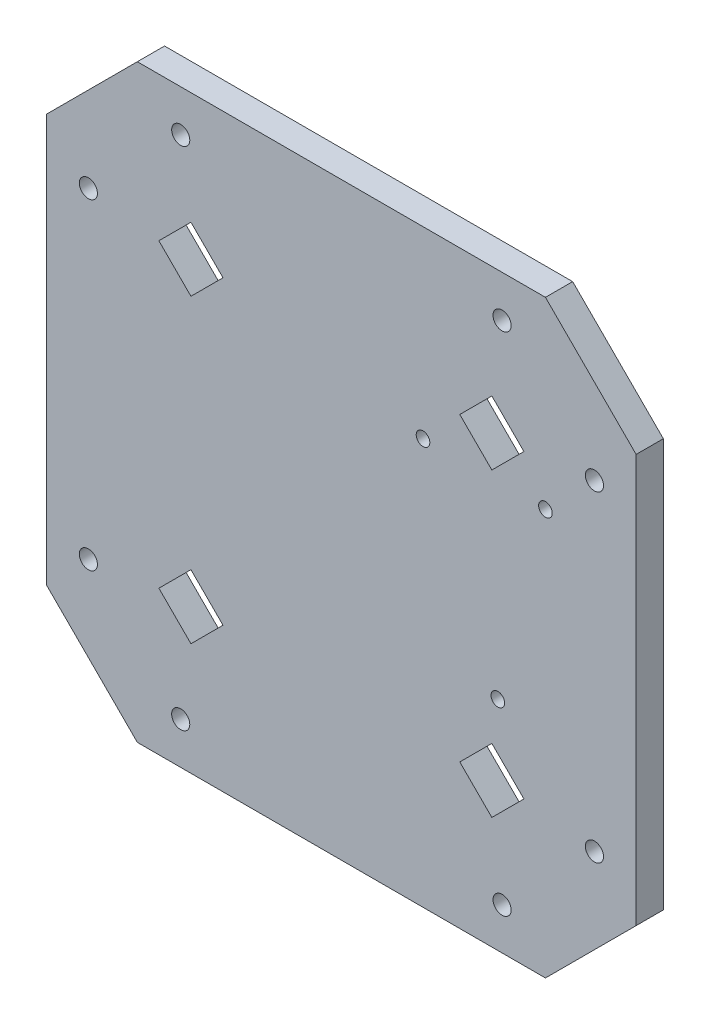
SolidWorks part; units mm, degrees
ref_plane "前基準面" through (0, 0, 0) normal (0, 0, 1) x (1, 0, 0)
ref_plane "上基準面" through (0, 0, 0) normal (0, 1, 0) x (1, 0, 0)
ref_plane "右基準面" through (0, 0, 0) normal (1, 0, 0) x (0, 0, -1)
sketch "草圖1" plane through (0, 0, 0) normal (0, 0, 1) x (1, 0, 0)
  line L2 (0, 0) -> (0, 130)
  line L4 (-130, 0) -> (-130, 130)
  line L5 (-130, 130) -> (0, 130)
  line L37 (-130, 0) -> (0, 0)
  dimension "D2" = 130
  dimension "D3" = 130
extrude "填料-伸長1" add sketch "草圖1" along normal blind 6
ref_plane "平面1" through (0, 0, -35.9) normal (0, 0, 1) x (1, 0, 0)
sketch "草圖10" plane through (0, 0, 6) normal (0, 0, 1) x (1, 0, 0)
  line L0 (0, 0) -> (0, 130) construction
  line L1 (-38.8909, 98.1802) -> (-31.8198, 105.2513)
  line L2 (-38.8909, 98.1802) -> (-31.8198, 91.1091)
  line L3 (-31.8198, 91.1091) -> (-24.7487, 98.1802)
  line L4 (-31.8198, 105.2513) -> (-24.7487, 98.1802)
  line L6 (-28.2843, 101.7157) -> (0, 130) construction
  line L8 (-65, 130) -> (-65, 0) construction
  line L9 (0, 130) -> (-130, 130) construction
  line L10 (-130, 0) -> (0, 0) construction
  line L11 (-101.7157, 101.7157) -> (-130, 130) construction
  line L12 (-130, 130) -> (-130, 0) construction
  line L13 (-130, 65) -> (0, 65) construction
  line L14 (-98.1802, 105.2513) -> (-105.2513, 98.1802)
  line L15 (-98.1802, 91.1091) -> (-105.2513, 98.1802)
  line L16 (-91.1091, 98.1802) -> (-98.1802, 91.1091)
  line L17 (-91.1091, 98.1802) -> (-98.1802, 105.2513)
  line L18 (-101.7157, 28.2843) -> (-130, 0) construction
  line L19 (-28.2843, 28.2843) -> (0, 0) construction
  line L20 (-91.1091, 31.8198) -> (-98.1802, 24.7487)
  line L21 (-91.1091, 31.8198) -> (-98.1802, 38.8909)
  line L22 (-98.1802, 38.8909) -> (-105.2513, 31.8198)
  line L23 (-98.1802, 24.7487) -> (-105.2513, 31.8198)
  line L24 (-31.8198, 24.7487) -> (-24.7487, 31.8198)
  line L25 (-31.8198, 38.8909) -> (-24.7487, 31.8198)
  line L26 (-38.8909, 31.8198) -> (-31.8198, 38.8909)
  line L27 (-38.8909, 31.8198) -> (-31.8198, 24.7487)
  dimension "D4" = 135
  dimension "D6" = 45
  dimension "D2" = 10
  dimension "D3" = 10
  dimension "D5" = 40
  dimension "D1" = 10
extrude "除料-伸長1" cut sketch "草圖10" against normal up to surface (6 mm away) up to face at (-65, 65, 0)
sketch "草圖11" plane through (0, 0, 6) normal (0, 0, 1) x (1, 0, 0)
  line L0 (-29.5647, 120.8) -> (-29.5647, 130) construction
  line L1 (0, 130) -> (-130, 130) construction
  line L2 (-65, 130) -> (-65, 0) construction
  line L3 (-130, 0) -> (0, 0) construction
  line L4 (-65, 0) -> (-130, 65) construction
  line L5 (-9.1804, 98.4354) -> (-9.2, 100.4353) construction
  line L6 (-9.2, 100.4353) -> (0, 100.4353) construction
  line L7 (0, 0) -> (0, 130) construction
  line L8 (-130, 130) -> (-130, 0) construction
  line L9 (-130, 65) -> (0, 65) construction
  line L10 (-120.8, 100.4353) -> (-130, 100.4353) construction
  line L11 (-120.8196, 98.4354) -> (-120.8, 100.4353) construction
  line L12 (-100.4353, 120.8) -> (-100.4353, 130) construction
  line L13 (-100.4353, 9.2) -> (-100.4353, 0) construction
  line L14 (-120.8196, 31.5646) -> (-120.8, 29.5647) construction
  line L15 (-120.8, 29.5647) -> (-130, 29.5647) construction
  line L16 (-9.2, 29.5647) -> (0, 29.5647) construction
  line L17 (-9.1804, 31.5646) -> (-9.2, 29.5647) construction
  line L18 (-29.5647, 9.2) -> (-29.5647, 0) construction
  circle A0 centre (-9.2, 100.4353) radius 2
  circle A1 centre (-29.5647, 120.8) radius 2
  circle A2 centre (-100.4353, 120.8) radius 2
  circle A3 centre (-120.8, 100.4353) radius 2
  circle A4 centre (-120.8, 29.5647) radius 2
  circle A5 centre (-100.4353, 9.2) radius 2
  circle A6 centre (-29.5647, 9.2) radius 2
  circle A7 centre (-9.2, 29.5647) radius 2
  dimension "D1" = 9.2
  dimension "D4" = 28.8
  dimension "D6" = 4
  dimension "D8" = 4
extrude "除料-伸長2" cut sketch "草圖11" against normal up to next
chamfer "導角1" distance 20 angle 45 4 edges at (0, 130, 3) (0, 0, 3) (-130, 0, 3) (-130, 130, 3)
sketch "草圖12" plane through (0, 0, 6) normal (0, 0, 1) x (1, 0, 0)
  line L0 (-47, 89.5) -> (-47, 40.5) construction
  line L1 (-47, 40.5) -> (-20, 40.5) construction
  line L2 (-20, 40.5) -> (-20, 89.5) construction
  line L3 (-20, 89.5) -> (-47, 89.5) construction
  line L4 (0, 20) -> (0, 110) construction
  circle A1 centre (-47, 89.5) radius 1.5
  circle A2 centre (-20, 89.5) radius 1.5
  circle A4 centre (-30.5, 48) radius 1.5
  point P8 (-20, 65)
  point P11 (0, 65)
  dimension "D1" = 3
  dimension "D6" = 10.5
  dimension "D7" = 7.5
  dimension "D2" = 49
  dimension "D3" = 27
  dimension "D4" = 0
  dimension "D5" = 20
extrude "除料-伸長3" cut sketch "草圖12" against normal up to next
sketch "草圖13" plane through (0, 0, 0) normal (0, 0, -1) x (-1, 0, 0)
  circle A0 centre (20, 89.5) radius 1.5
  circle A1 centre (20, 89.5) radius 4
  circle A2 centre (47, 89.5) radius 4
  circle A3 centre (47, 89.5) radius 1.5
  circle A4 centre (30.5, 48) radius 4
  circle A5 centre (30.5, 48) radius 1.5
  dimension "D1" = 8
  dimension "D2" = 8
  dimension "D3" = 8
extrude "填料-伸長2" add sketch "草圖13" along normal blind 5
